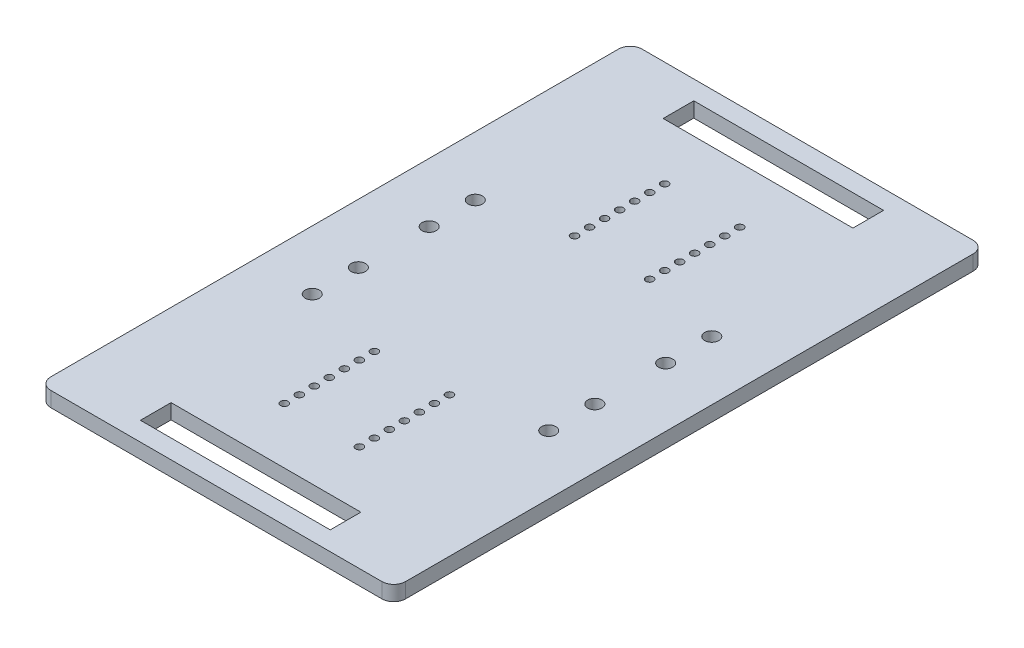
SolidWorks part; units mm, degrees
ref_plane "Front Plane" through (0, 0, 0) normal (0, 0, 1) x (1, 0, 0)
ref_plane "Top Plane" through (0, 0, 0) normal (0, 1, 0) x (1, 0, 0)
ref_plane "Right Plane" through (0, 0, 0) normal (1, 0, 0) x (0, 0, -1)
sketch "Sketch1" plane through (0, 0, 0) normal (0, 1, 0) x (1, 0, 0)
  line L0 (0, -125) -> (0, 0) construction
  line L1 (0, 125) -> (150, 125)
  line L2 (0, -125) -> (0, 125)
  line L3 (0, -125) -> (150, -125)
  line L4 (150, 125) -> (150, -125)
  line L5 (0, 0) -> (0, 125) construction
  dimension "D1" = 150
  dimension "D3" = 250
extrude "Boss-Extrude1" add sketch "Sketch1" against normal blind 6.35
sketch "Sketch2" plane through (0, 0, 0) normal (0, 1, 0) x (1, 0, 0)
  line L0 (59.125, -80.424) -> (59.125, -74.074) construction
  line L1 (75, 0) -> (75, -104.046) construction
  line L2 (34.868, -104.046) -> (115.132, -104.046)
  line L3 (34.868, -104.046) -> (34.868, -117)
  line L4 (34.868, -117) -> (115.132, -117)
  line L5 (115.132, -104.046) -> (115.132, -117)
  line L6 (34.868, 104.046) -> (115.132, 104.046)
  line L7 (34.868, 104.046) -> (34.868, 117)
  line L8 (34.868, 117) -> (115.132, 117)
  line L9 (115.132, 104.046) -> (115.132, 117)
  line L10 (75, 0) -> (75, 104.046) construction
  line L11 (59.125, -74.074) -> (59.125, -67.724) construction
  line L12 (59.125, -67.724) -> (59.125, -61.374) construction
  line L13 (59.125, -61.374) -> (59.125, -55.024) construction
  line L14 (59.125, -55.024) -> (59.125, -48.674) construction
  line L15 (59.125, -48.674) -> (59.125, -42.324) construction
  line L16 (90.875, -80.424) -> (90.875, -74.074) construction
  line L17 (90.875, -74.074) -> (90.875, -67.724) construction
  line L18 (90.875, -67.724) -> (90.875, -61.374) construction
  line L19 (90.875, -61.374) -> (90.875, -55.024) construction
  line L20 (90.875, -55.024) -> (90.875, -48.674) construction
  line L21 (90.875, -48.674) -> (90.875, -42.324) construction
  line L22 (59.125, -80.424) -> (90.875, -80.424) construction
  line L23 (59.125, -42.324) -> (90.875, -42.324) construction
  line L24 (59.125, 42.324) -> (59.125, 48.674) construction
  line L25 (59.125, 48.674) -> (59.125, 55.024) construction
  line L26 (59.125, 55.024) -> (59.125, 61.374) construction
  line L27 (59.125, 61.374) -> (59.125, 67.724) construction
  line L28 (59.125, 67.724) -> (59.125, 74.074) construction
  line L29 (59.125, 74.074) -> (59.125, 80.424) construction
  line L30 (90.875, 42.324) -> (90.875, 48.674) construction
  line L31 (90.875, 48.674) -> (90.875, 55.024) construction
  line L32 (90.875, 55.024) -> (90.875, 61.374) construction
  line L33 (90.875, 61.374) -> (90.875, 67.724) construction
  line L34 (90.875, 67.724) -> (90.875, 74.074) construction
  line L35 (90.875, 74.074) -> (90.875, 80.424) construction
  line L36 (59.125, 80.424) -> (90.875, 80.424) construction
  line L37 (59.125, 42.324) -> (90.875, 42.324) construction
  line L38 (59.125, 61.374) -> (75, 61.374) construction
  line L39 (75, 61.374) -> (90.875, 61.374) construction
  line L40 (0, -125) -> (0, 125) construction
  line L41 (0, 0) -> (75, 0) construction
  line L42 (150, 125) -> (0, 125) construction
  line L43 (0, -125) -> (150, -125) construction
  line L45 (75, 125) -> (75, -125) construction
  line L46 (0, 125) -> (150, 125) construction
  line L47 (0, -125) -> (150, -125) construction
  circle A1 centre (59.125, -80.424) radius 1.5875
  circle A2 centre (59.125, -74.074) radius 1.5875
  circle A3 centre (59.125, -67.724) radius 1.5875
  circle A4 centre (59.125, -61.374) radius 1.5875
  circle A5 centre (59.125, -55.024) radius 1.5875
  circle A6 centre (59.125, -48.674) radius 1.5875
  circle A7 centre (59.125, -42.324) radius 1.5875
  circle A8 centre (90.875, -80.424) radius 1.5875
  circle A9 centre (90.875, -74.074) radius 1.5875
  circle A10 centre (90.875, -67.724) radius 1.5875
  circle A11 centre (90.875, -61.374) radius 1.5875
  circle A12 centre (90.875, -55.024) radius 1.5875
  circle A13 centre (90.875, -48.674) radius 1.5875
  circle A14 centre (90.875, -42.324) radius 1.5875
  circle A15 centre (59.125, 80.424) radius 1.5875
  circle A16 centre (59.125, 74.074) radius 1.5875
  circle A17 centre (59.125, 67.724) radius 1.5875
  circle A18 centre (59.125, 61.374) radius 1.5875
  circle A19 centre (59.125, 55.024) radius 1.5875
  circle A20 centre (59.125, 48.674) radius 1.5875
  circle A21 centre (59.125, 42.324) radius 1.5875
  circle A22 centre (90.875, 80.424) radius 1.5875
  circle A23 centre (90.875, 74.074) radius 1.5875
  circle A24 centre (90.875, 67.724) radius 1.5875
  circle A25 centre (90.875, 61.374) radius 1.5875
  circle A26 centre (90.875, 55.024) radius 1.5875
  circle A27 centre (90.875, 48.674) radius 1.5875
  circle A28 centre (90.875, 42.324) radius 1.5875
  dimension "D6" = 3.175
  dimension "D7" = 6.35
  dimension "D8" = 15.875
  dimension "D10" = 3.175
  dimension "D1" = 12.954
  dimension "D2" = 80.264
  dimension "D3" = 8
  dimension "D4" = 23.622
  dimension "D5" = 15.875
  dimension "D9" = 15.875
  dimension "D11" = 6.35
  dimension "D12" = 23.622
  dimension "D13" = 84.648
  dimension "D14" = 234
extrude "Cut-Extrude1" cut sketch "Sketch2" against normal through all
sketch "Sketch3" plane through (0, 0, 0) normal (0, 1, 0) x (1, 0, 0)
  line L0 (0, 0) -> (75, 0) construction
  line L1 (0, 0) -> (150, 0) construction
  line L2 (0, -125) -> (0, 125) construction
  line L3 (150, 125) -> (150, -125) construction
  line L4 (75, 125) -> (75, -125) construction
  line L5 (0, -125) -> (150, -125) construction
  line L6 (0, 125) -> (150, 125) construction
  circle A0 centre (25, -14.975) radius 3
  circle A1 centre (25, -34.475) radius 3
  circle A2 centre (25, 14.975) radius 3
  circle A3 centre (25, 34.475) radius 3
  circle A4 centre (125, -14.975) radius 3
  circle A5 centre (125, -34.475) radius 3
  circle A6 centre (125, 14.975) radius 3
  circle A7 centre (125, 34.475) radius 3
  dimension "D3" = 6
  dimension "D1" = 34.475
  dimension "D2" = 19.5
  dimension "D4" = 100
extrude "Cut-Extrude2" cut sketch "Sketch3" against normal through all
fillet "Fillet1" radius 5 4 edges at (150, -3.175, -125) (0, -3.175, -125) (150, -3.175, 125) (0, -3.175, 125)
